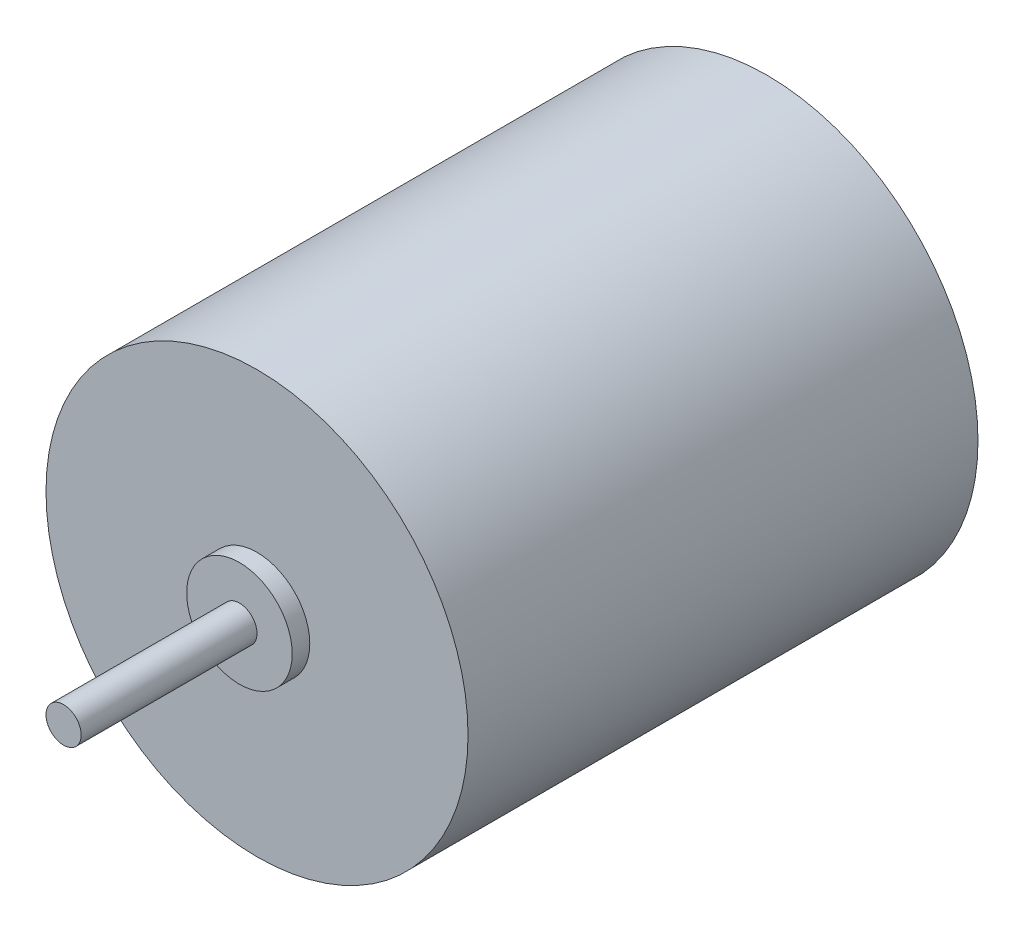
SolidWorks part; units mm, degrees
ref_plane "Front Plane" through (0, 0, 0) normal (0, 0, 1) x (1, 0, 0)
ref_plane "Top Plane" through (0, 0, 0) normal (0, 1, 0) x (1, 0, 0)
ref_plane "Right Plane" through (0, 0, 0) normal (1, 0, 0) x (0, 0, -1)
sketch "Sketch1" plane through (0, 0, 0) normal (0, 0, 1) x (1, 0, 0)
  circle A0 centre (0, 0) radius 12
  dimension "D1" = 24
extrude "Boss-Extrude1" add sketch "Sketch1" along normal blind 29
sketch "Sketch2" plane through (0, 0, 29) normal (0, 0, 1) x (1, 0, 0)
  circle A0 centre (0, 0) radius 3
  dimension "D1" = 6
extrude "Boss-Extrude2" add sketch "Sketch2" along normal blind 1
sketch "Sketch3" plane through (0, 0, 30) normal (0, 0, 1) x (1, 0, 0)
  circle A0 centre (0, 0) radius 1
  dimension "D1" = 2
extrude "Boss-Extrude3" add sketch "Sketch3" along normal blind 10 contours A0
